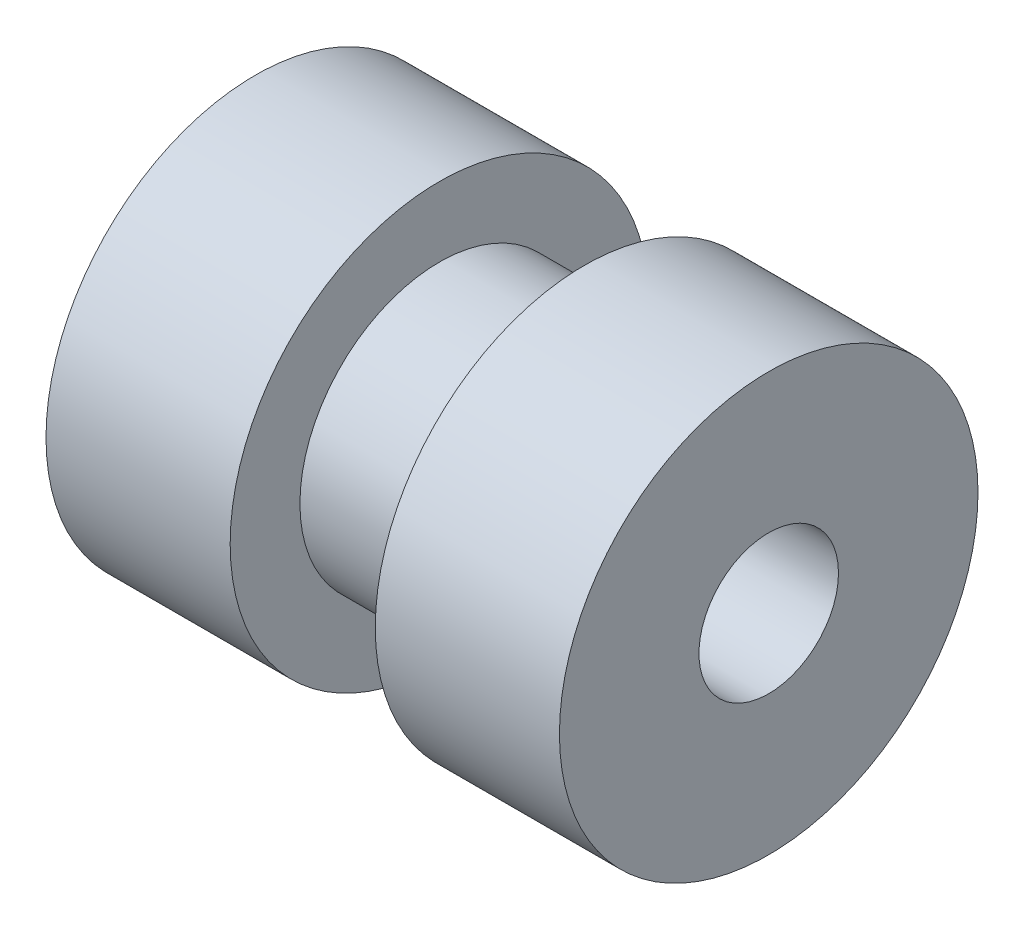
SolidWorks part; units mm, degrees
material "Silicon Rubber"
ref_plane "Front Plane" through (0, 0, 0) normal (0, 0, 1) x (1, 0, 0)
ref_plane "Top Plane" through (0, 0, 0) normal (0, 1, 0) x (1, 0, 0)
ref_plane "Right Plane" through (0, 0, 0) normal (1, 0, 0) x (0, 0, -1)
sketch "Sketch1" plane through (0, 0, 0) normal (1, 0, 0) x (0, 0, -1)
  circle A0 centre (0, 0) radius 3.175
  circle A1 centre (0, 0) radius 9.525
  dimension "D1" = 6.35
  dimension "D2" = 19.05
extrude "Boss-Extrude1" add sketch "Sketch1" along normal blind 8.382
sketch "Sketch2" plane through (8.382, 0, 0) normal (1, 0, 0) x (0, 0, -1)
  circle A0 centre (0, 0) radius 3.175
  circle A1 centre (0, 0) radius 6.35
  dimension "D1" = 12.7
extrude "Boss-Extrude2" add sketch "Sketch2" along normal blind 6.604
sketch "Sketch3" plane through (14.986, 0, 0) normal (1, 0, 0) x (0, 0, -1)
  circle A0 centre (0, 0) radius 3.175
  circle A1 centre (0, 0) radius 9.525
extrude "Boss-Extrude3" add sketch "Sketch3" along normal blind 8.382
